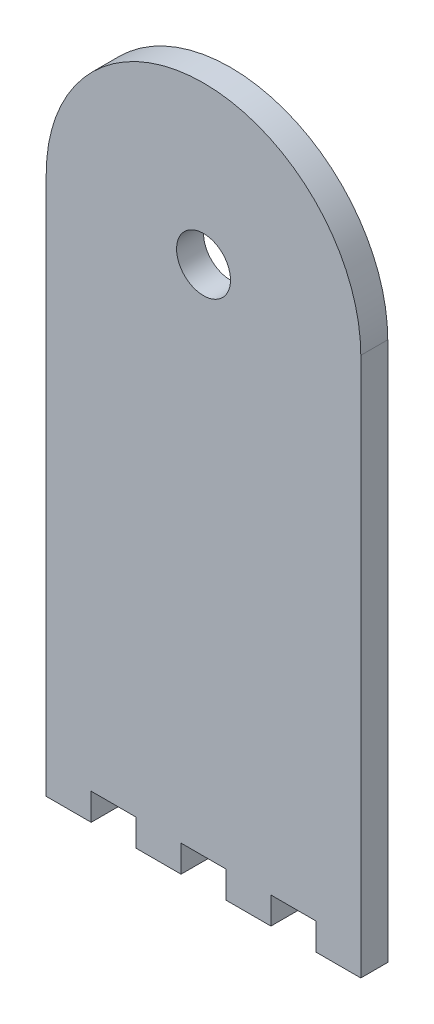
SolidWorks part; units mm, degrees
ref_plane "Alzado" through (0, 0, 0) normal (0, 0, 1) x (1, 0, 0)
ref_plane "Planta" through (0, 0, 0) normal (0, 1, 0) x (1, 0, 0)
ref_plane "Vista lateral" through (0, 0, 0) normal (1, 0, 0) x (0, 0, -1)
sketch "Croquis1" plane through (0, 0, 0) normal (0, 0, 1) x (1, 0, 0)
  line L0 (0, -60) -> (0, 0)
  line L1 (0, 0) -> (35, 0) construction
  line L2 (35, 0) -> (35, -60)
  line L3 (35, -60) -> (30, -60)
  line L4 (30, -60) -> (30, -57)
  line L5 (30, -57) -> (25, -57)
  line L6 (25, -57) -> (25, -60)
  line L7 (25, -60) -> (20, -60)
  line L8 (20, -60) -> (20, -57)
  line L9 (20, -57) -> (15, -57)
  line L10 (15, -57) -> (15, -60)
  line L11 (15, -60) -> (10, -60)
  line L12 (10, -60) -> (10, -57)
  line L13 (10, -57) -> (5, -57)
  line L14 (5, -57) -> (5, -60)
  line L15 (5, -60) -> (0, -60)
  arc A0 (0, 0) -> (35, 0) centre (17.5, 0) cw
  circle A1 centre (17.5, 0) radius 3
  dimension "D10" = 6
  dimension "D1" = 60
  dimension "D2" = 3
  dimension "D3" = 5
  dimension "D4" = 5
  dimension "D5" = 5
  dimension "D6" = 5
  dimension "D7" = 5
  dimension "D8" = 5
  dimension "D9" = 5
extrude "Saliente-Extruir1" add sketch "Croquis1" along normal blind 3
